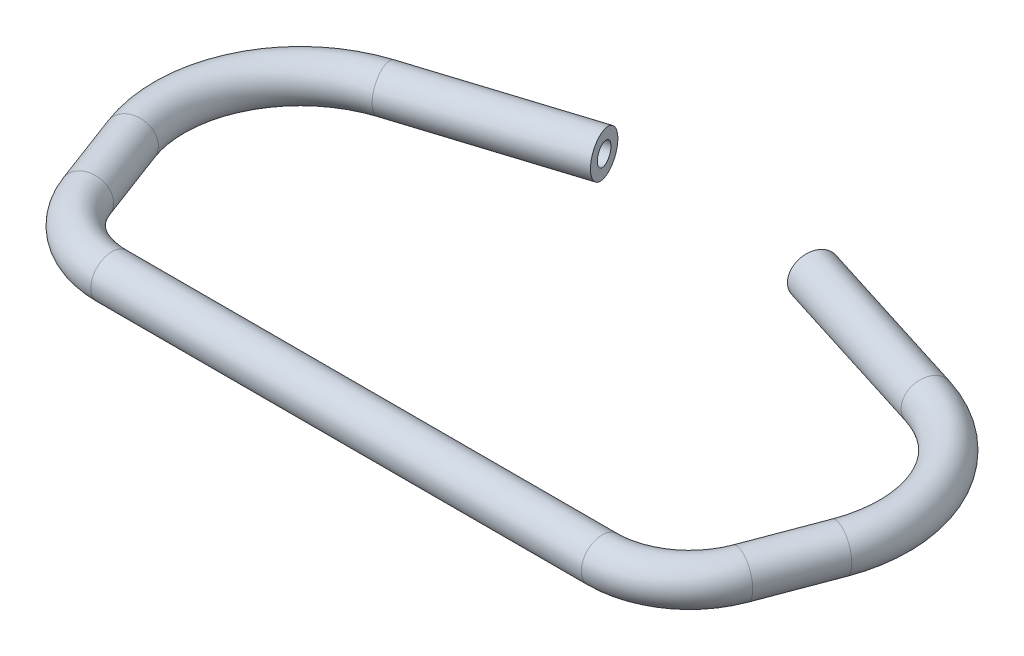
SolidWorks part; units mm, degrees
material "1060 Alloy"
ref_plane "Plano frontal" through (0, 0, 0) normal (0, 0, 1) x (1, 0, 0)
ref_plane "Plano superior" through (0, 0, 0) normal (0, 1, 0) x (1, 0, 0)
ref_plane "Plano direito" through (0, 0, 0) normal (1, 0, 0) x (0, 0, -1)
sketch "Sketch2" plane through (0, 0, 0) normal (0, 1, 0) x (1, 0, 0)
  line L7 (140.394, 0) -> (-140.394, 0)
  line L15 (187.1895, 32.3881) -> (175, 0) construction
  line L16 (-187.1895, 32.3881) -> (-202.6933, 73.5821)
  line L17 (-187.1895, 32.3881) -> (-175, 0) construction
  line L18 (-155.0529, 171.5288) -> (-60, 201.4988)
  line L19 (0, -55) -> (0, 55) construction
  line L20 (155.0529, 171.5288) -> (60, 201.4988)
  line L21 (-140.394, 0) -> (-175, 0) construction
  line L22 (187.1895, 32.3881) -> (202.6933, 73.5821)
  line L23 (140.394, 0) -> (175, 0) construction
  arc A0 (-202.6933, 73.5821) -> (-155.0529, 171.5288) centre (-132.5, 100) cw
  arc A3 (202.6933, 73.5821) -> (155.0529, 171.5288) centre (132.5, 100) ccw
  arc A5 (-187.1895, 32.3881) -> (-140.394, 0) centre (-140.394, 50) ccw
  arc A6 (187.1895, 32.3881) -> (140.394, 0) centre (140.394, 50) cw
  point P8 (0, 0)
  point P18 (-459.9821, 321.7688)
  dimension "D1" = 350
  dimension "D2" = 120
  dimension "D3" = 75
  dimension "D4" = 100
  dimension "D5" = 265
  dimension "D6" = 145
  dimension "D7" = 42.5
  dimension "D8" = 50
sketch "Sketch3" plane through (0, 0, 0) normal (1, 0, 0) x (0, 0, -1)
  circle A0 centre (0, 0) radius 12
  circle A1 centre (0, 0) radius 6
  dimension "D1" = 24
  dimension "D2" = 12
sweep "Sweep7" add profiles "Sketch3" path "Sketch2"
